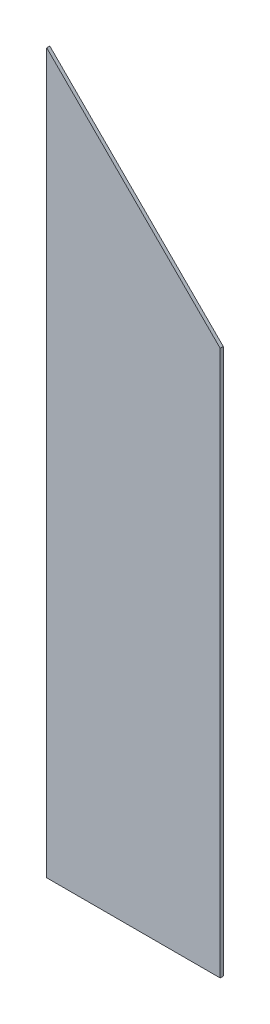
SolidWorks part; units mm, degrees
material "Glass"
ref_plane "Front Plane" through (0, 0, 0) normal (0, 0, 1) x (1, 0, 0)
ref_plane "Top Plane" through (0, 0, 0) normal (0, 1, 0) x (1, 0, 0)
ref_plane "Right Plane" through (0, 0, 0) normal (1, 0, 0) x (0, 0, -1)
sketch "Sketch1" plane through (0, 0, 0) normal (0, 0, 1) x (1, 0, 0)
  line L1 (0, 0) -> (177.8, 0)
  line L2 (0, 0) -> (0, 736.6)
  line L3 (0, 736.6) -> (177.8, 558.8)
  line L4 (177.8, 0) -> (177.8, 558.8)
  dimension "D1" = 177.8
  dimension "D2" = 736.6
  dimension "D3" = 558.8
extrude "Boss-Extrude1" add sketch "Sketch1" along normal blind 3.175
